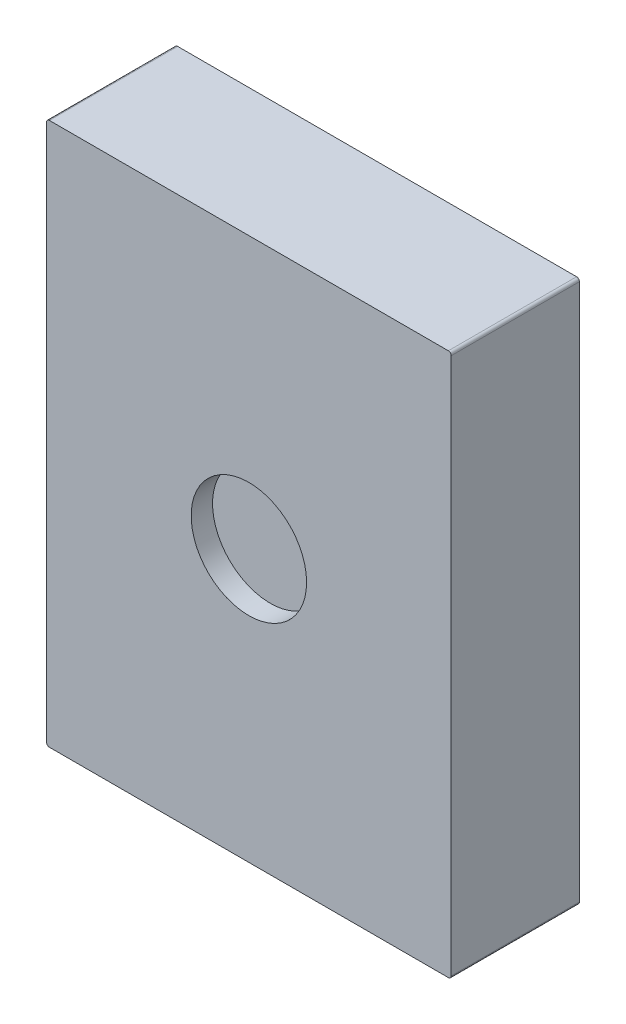
SolidWorks part; units mm, degrees
ref_plane "Front Plane" through (0, 0, 0) normal (0, 0, 1) x (1, 0, 0)
ref_plane "Top Plane" through (0, 0, 0) normal (0, 1, 0) x (1, 0, 0)
ref_plane "Right Plane" through (0, 0, 0) normal (1, 0, 0) x (0, 0, -1)
sketch "Sketch1" plane through (0, 0, 0) normal (0, 0, 1) x (1, 0, 0)
  line L1 (-142, 190.5) -> (142, 190.5)
  line L2 (-142, 190.5) -> (-142, -190.5)
  line L3 (-142, -190.5) -> (142, -190.5)
  line L4 (142, 190.5) -> (142, -190.5)
  line L5 (-142, 190.5) -> (142, -190.5) construction
  line L6 (-142, -190.5) -> (142, 190.5) construction
  point P0 (0, 0)
  dimension "D1" = 284
  dimension "D2" = 381
extrude "Boss-Extrude1" add sketch "Sketch1" along normal blind 60
sketch "Sketch3" plane through (0, 0, 60) normal (0, 0, 1) x (1, 0, 0)
  line L0 (-142, 190.5) -> (142, -190.5) construction
  line L2 (-142, 190.5) -> (142, 190.5)
  line L3 (-142, 190.5) -> (-142, -190.5)
  line L4 (-142, -190.5) -> (142, -190.5)
  line L5 (142, 190.5) -> (142, -190.5)
  line L6 (-142, 190.5) -> (142, -190.5) construction
  line L7 (-142, -190.5) -> (142, 190.5) construction
  point P4 (0, 0)
extrude "Boss-Extrude2" add sketch "Sketch3" along normal blind 30
sketch "Sketch4" plane through (0, 0, 90) normal (0, 0, 1) x (1, 0, 0)
  circle A0 centre (0, 0) radius 40.5
  dimension "D1" = 81
extrude "Cut-Extrude1" cut sketch "Sketch4" against normal blind 15
shell "Shell1" thickness 10
fillet "Fillet1" radius 2 4 edges at (-142, -190.5, 45) (142, -190.5, 45) (142, 190.5, 45) (-142, 190.5, 45)
